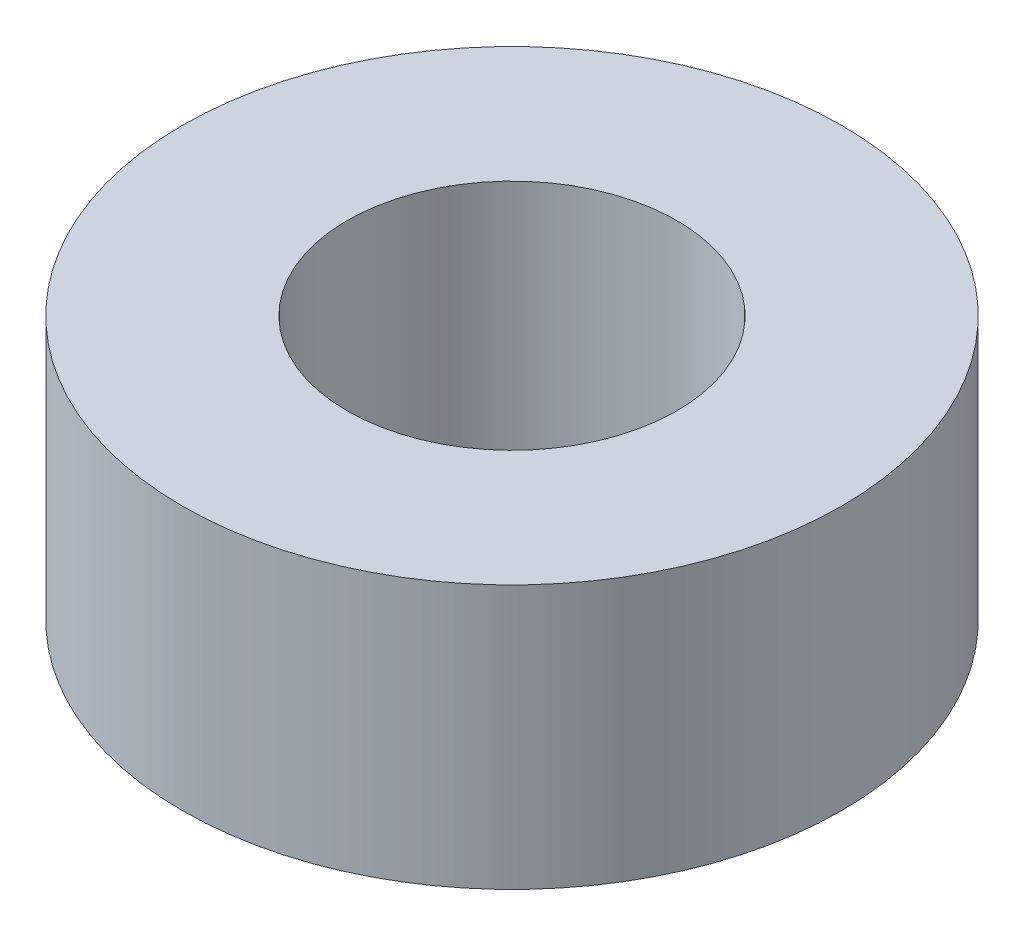
SolidWorks part; units mm, degrees
material "acero"
ref_plane "Alzado" through (0, 0, 0) normal (0, 0, 1) x (1, 0, 0)
ref_plane "Planta" through (0, 0, 0) normal (0, 1, 0) x (1, 0, 0)
ref_plane "Vista lateral" through (0, 0, 0) normal (1, 0, 0) x (0, 0, -1)
sketch "Croquis1" plane through (0, 0, 0) normal (0, 1, 0) x (1, 0, 0)
  circle A0 centre (0, 0) radius 5
  circle A1 centre (0, 0) radius 2.5
  dimension "D1" = 10
  dimension "D2" = 5
extrude "Saliente-Extruir1" add sketch "Croquis1" along normal blind 4
